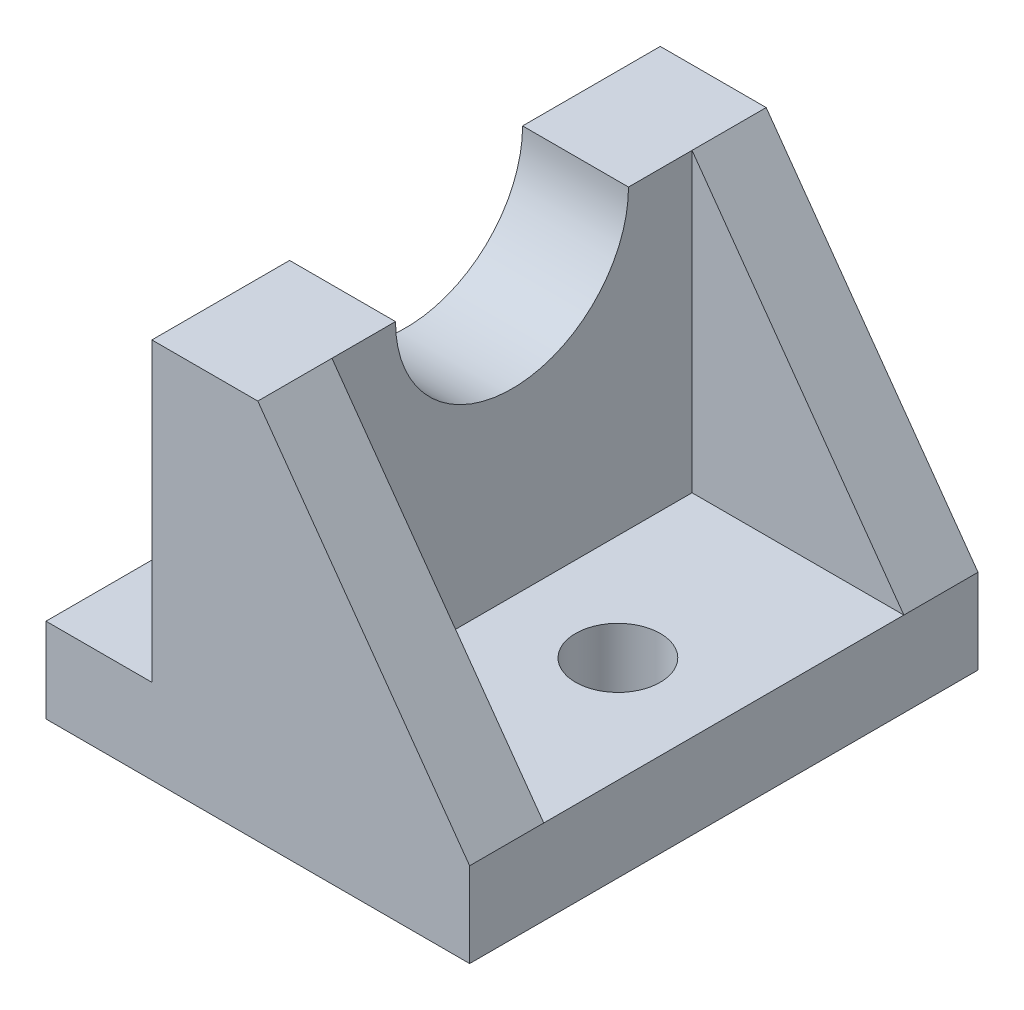
SolidWorks part; units mm, degrees
ref_plane "Спереди" through (0, 0, 0) normal (0, 0, 1) x (1, 0, 0)
ref_plane "Сверху" through (0, 0, 0) normal (0, 1, 0) x (1, 0, 0)
ref_plane "Справа" through (0, 0, 0) normal (1, 0, 0) x (0, 0, -1)
sketch "Эскиз1" plane through (0, 0, 0) normal (0, 0, 1) x (1, 0, 0)
  line L0 (0, 45) -> (50, -25)
  line L1 (-50, -45) -> (50, -45)
  line L2 (-50, -45) -> (-50, 45)
  line L3 (-50, 45) -> (50, 45)
  line L4 (50, -45) -> (50, 45)
  line L5 (-50, -45) -> (50, 45) construction
  line L6 (-50, 45) -> (50, -45) construction
  line L7 (-50, 45) -> (-25, 45)
  line L8 (-50, 45) -> (-50, -25)
  line L9 (-50, -25) -> (-25, -25)
  line L10 (-25, 45) -> (-25, -25)
  point P0 (0, 0)
  dimension "D1" = 100
  dimension "D2" = 90
  dimension "D3" = 20
  dimension "D4" = 25
extrude "Бобышка-Вытянуть1" add sketch "Эскиз1" along normal mid plane 120 contours L3 L10 L9 L2 L1 L4 L0
sketch "Эскиз2" plane through (0, 45, 0) normal (0, 1, 0) x (1, 0, 0)
  line L0 (0, 0) -> (50, 0) construction
  line L1 (0, -60) -> (0, 60) construction
  line L2 (50, -60) -> (50, 60) construction
  line L4 (0, -42.5) -> (50, -42.5)
  line L5 (0, -42.5) -> (0, 42.5)
  line L6 (0, 42.5) -> (50, 42.5)
  line L7 (50, -42.5) -> (50, 42.5)
  line L8 (0, -42.5) -> (50, 42.5) construction
  line L9 (0, 42.5) -> (50, -42.5) construction
  point P6 (25, 0)
  dimension "D1" = 85
extrude "Вырез-Вытянуть1" cut sketch "Эскиз2" against normal up to surface (70 mm away) up to face at (-37.5, -25, 0)
sketch "Эскиз3" plane through (0, -25, 0) normal (0, 1, 0) x (1, 0, 0)
  line L0 (0, 0) -> (50, 0) construction
  line L1 (0, -42.5) -> (0, 42.5) construction
  line L2 (50, 42.5) -> (50, -42.5) construction
  circle A0 centre (25, 0) radius 10
  dimension "D1" = 20
extrude "Вырез-Вытянуть2" cut sketch "Эскиз3" against normal through all
sketch "Эскиз4" plane through (-25, 0, 0) normal (-1, 0, 0) x (0, 0, 1)
  line L0 (60, 45) -> (-60, 45) construction
  circle A0 centre (0, 45) radius 27.5
  dimension "D1" = 55
extrude "Вырез-Вытянуть3" cut sketch "Эскиз4" against normal through all
